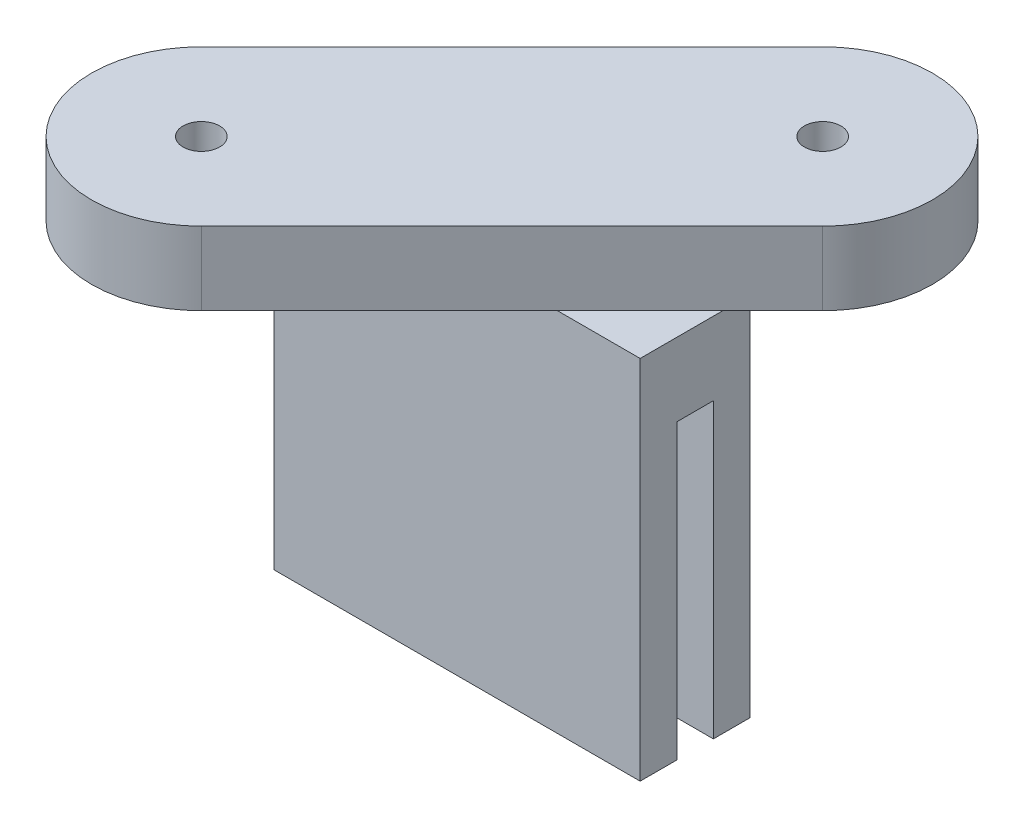
SolidWorks part; units mm, degrees
ref_plane "Alzado" through (0, 0, 0) normal (0, 0, 1) x (1, 0, 0)
ref_plane "Planta" through (0, 0, 0) normal (0, 1, 0) x (1, 0, 0)
ref_plane "Vista lateral" through (0, 0, 0) normal (1, 0, 0) x (0, 0, -1)
sketch "Croquis1" plane through (0, 0, 0) normal (0, 1, 0) x (1, 0, 0)
  line L0 (-38.8909, -45.9619) -> (-45.9619, -38.8909) construction
  line L1 (42.4264, 42.4264) -> (-42.4264, -42.4264) construction
  line L2 (63.6396, 21.2132) -> (-21.2132, -63.6396)
  line L3 (21.2132, 63.6396) -> (-63.6396, -21.2132)
  line L4 (0, 0) -> (0, 82.3109) construction
  circle A0 centre (-42.4264, -42.4264) radius 5
  circle A1 centre (42.4264, 42.4264) radius 5
  arc A2 (63.6396, 21.2132) -> (21.2132, 63.6396) centre (42.4264, 42.4264) ccw
  arc A3 (-63.6396, -21.2132) -> (-21.2132, -63.6396) centre (-42.4264, -42.4264) ccw
  point P6 (0, 0)
  point P11 (0, 0)
  dimension "D1" = 10
  dimension "D3" = 10
  dimension "D5" = 30
  dimension "D2" = 120
  dimension "D4" = 45
extrude "Saliente-Extruir1" add sketch "Croquis1" along normal blind 20
sketch "Croquis2" plane through (0, 0, 0) normal (0, -1, 0) x (1, 0, 0)
  line L7 (-50, 15) -> (50, 15)
  line L11 (-50, -15) -> (50, -15)
  line L16 (-50, 15) -> (-50, -15)
  line L17 (50, -15) -> (50, 15)
  point P0 (0, 0)
  dimension "D1" = 15
  dimension "D2" = 15
  dimension "D3" = 100
  dimension "D4" = 50
  dimension "D5" = 30
extrude "Saliente-Extruir2" add sketch "Croquis2" along normal blind 100
sketch "Croquis3" plane through (0, -100, 0) normal (0, -1, 0) x (1, 0, 0)
  line L0 (-50, 15) -> (-50, -15) construction
  line L1 (50, -5) -> (-50, -5)
  line L2 (50, -5) -> (50, 5)
  line L3 (50, 5) -> (-50, 5)
  line L4 (-50, -5) -> (-50, 5)
  line L5 (50, -5) -> (-50, 5) construction
  line L6 (50, 5) -> (-50, -5) construction
  point P0 (0, 0)
  dimension "D1" = 10
extrude "Cortar-Extruir1" cut sketch "Croquis3" against normal blind 80
